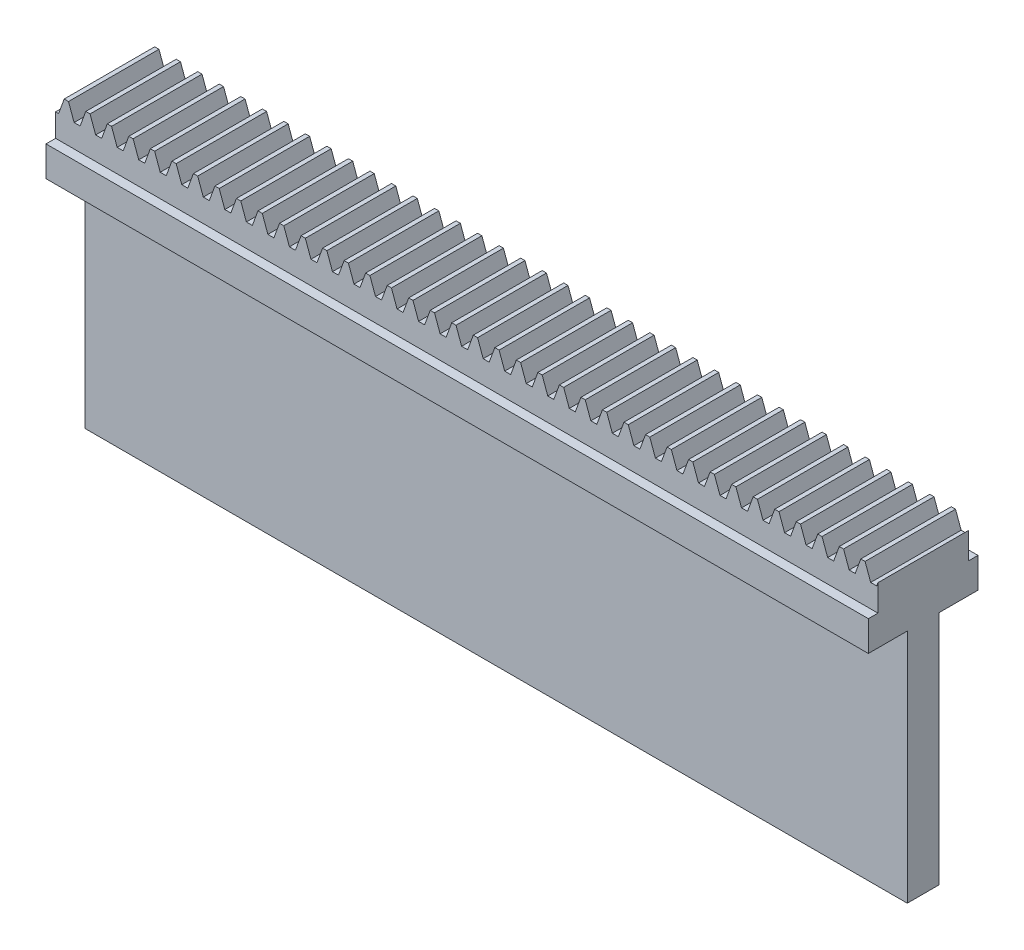
SolidWorks part; units mm, degrees
extrude "Blank" add sketch "BlankSke" against normal blind 20
sketch "BlankSke" plane through (0, 0, 0) normal (0, 0, 1) x (1, 0, 0)
  line L1 (0, 0) -> (150, 0)
  line L2 (0, 0) -> (0, 12.5)
  line L3 (0, 12.5) -> (150, 12.5)
  line L4 (150, 0) -> (150, 12.5)
  dimension "Length" = 150
  dimension "Blank_height" = 12.5
ref_plane "Plane1" through (0, 0, 0) normal (0, 0, 1) x (1, 0, 0)
ref_plane "Plane2" through (0, 0, 0) normal (0, 1, 0) x (1, 0, 0)
ref_plane "Plane3" through (0, 0, 0) normal (1, 0, 0) x (0, 0, -1)
other "Configuration Table"
sketch "HoldingSke" plane through (0, 0, 0) normal (0, 1, 0) x (1, 0, 0)
  line L0 (0, 0) -> (0.1113, 0.7922)
  line L1 (-15, 0) -> (100, 0) construction
  line L2 (0, 0) -> (-2.1039, 2.3779)
  line L3 (0, 0) -> (-11.863, 4.5341)
  line L4 (0, 0) -> (6.6156, 5.5511)
  line L5 (0, 0) -> (-23.7986, -8.8762)
  line L6 (0, 0) -> (-10.5278, -7.1032)
  line L9 (-71.009, 38.7566) -> (69.9449, 90.0596)
  line L10 (-76.2, 3.6279) -> (-64.95, 3.6279)
  line L11 (0, 0) -> (-7, 0)
  line L12 (-76.2, 101.6) -> (-76.155, 101.6)
  line L13 (24.9733, 27.94) -> (52.9518, 28.4284)
  line L14 (24.9733, 27.94) -> (24.9743, 27.94)
  line L15 (24.9733, 27.94) -> (100.4006, 29.5858)
  circle A0 centre (0, 0) radius 19.05
  circle A1 centre (0, 0) radius 5.625
  circle A2 centre (0, 0) radius 12.7
  dimension "MPH" = 11.25
  dimension "Diameter" = 38.1
  dimension "Num_teeth" = 40
  dimension "Pitch" = 0.8
  dimension "Show_teeth" = 998
  dimension "Thickness" = 12.7
  dimension "Ap" = 20
  dimension "Pitch_height" = 11.25
  dimension "Width" = 7
  dimension "Backlash" = 0.045
  dimension "Addendum_fac" = 1
  dimension "Dedendum_fac" = 1.25
  dimension "Clearance_fac" = 0.25
  dimension "Dedendum_add" = 0.001
  dimension "Length" = 150
  dimension "Module" = 1.25
sketch "TooCutSkeIll" plane through (0, 0, 0) normal (0, 0, 1) x (1, 0, 0)
  line L0 (-1.5597, 12.4671) -> (-0.6231, 9.8938)
  line L1 (-0.3285, 9.6875) -> (0.3285, 9.6875)
  line L2 (0.6231, 9.8938) -> (1.5597, 12.4671)
  line L3 (150, 12.5) -> (0, 12.5) construction
  line L4 (0, 0) -> (0, 64.897) construction
  line L5 (-13.208, 11.25) -> (12.954, 11.25) construction
  line L6 (0, 0) -> (150, 0) construction
  line L7 (1.1167, 11.25) -> (1.1167, 48.7463) construction
  line L8 (-1.1167, 11.25) -> (-1.1167, 48.7463) construction
  line L9 (1.6067, 12.5) -> (1.6067, 12.5254)
  line L10 (-1.6067, 12.5) -> (-1.6067, 12.5254)
  line L11 (-1.6067, 12.5254) -> (1.6067, 12.5254)
  arc A0 (0.3285, 9.6875) -> (0.6231, 9.8938) centre (0.3285, 10.001) ccw
  arc A1 (-0.6231, 9.8938) -> (-0.3285, 9.6875) centre (-0.3285, 10.001) ccw
  arc A2 (1.6067, 12.5) -> (1.5597, 12.4671) centre (1.6067, 12.45) ccw
  arc A3 (-1.5597, 12.4671) -> (-1.6067, 12.5) centre (-1.6067, 12.45) ccw
  dimension "Pitch_height" = 11.25
  dimension "Addendum_plus" = 1.2754
  dimension "Pressure_angle" = 20
  dimension "Gap_width" = 2.2335
  dimension "Dedendum" = 1.5625
extrude "ToothCutIll" [suppressed] cut sketch "TooCutSkeIll" against normal through all
sketch "TooCutSkeSim" plane through (0, 0, 0) normal (0, 0, 1) x (1, 0, 0)
  line L0 (0.548, 9.6875) -> (-0.548, 9.6875)
  line L1 (1.581, 12.5254) -> (0.548, 9.6875)
  line L2 (0, 17.4625) -> (0, 53.467) construction
  line L3 (1.581, 12.5254) -> (-1.581, 12.5254)
  line L6 (-1.581, 12.5254) -> (-0.548, 9.6875)
  line L9 (-1.1167, 11.25) -> (1.1167, 11.25) construction
  line L10 (0, 0) -> (150, 0) construction
  line L11 (1.1167, 11.25) -> (1.1167, 53.467) construction
  line L12 (-1.1167, 11.25) -> (-1.1167, 53.467) construction
  dimension "Pitch_height" = 11.25
  dimension "Addendum_plus" = 1.2754
  dimension "Pressure_angle" = 20
  dimension "Gap_width" = 2.2335
  dimension "Dedendum" = 1.5625
extrude "ToothCutSim" cut sketch "TooCutSkeSim" against normal through all
pattern_linear "TeethCuts" count 39 spacing 3.927 along (1, 0, 0) of "ToothCutIll", "ToothCutSim"
sketch "Croquis3" plane through (0, 0, 0) normal (0, 0, 1) x (1, 0, 0)
  line L0 (0, 9.6875) -> (0, 0) construction
  line L1 (0, 5.5) -> (150.5773, 5.5)
  line L2 (0, 5.5) -> (0, 12.8527)
  line L3 (0, 12.8527) -> (150.5773, 12.8527)
  line L4 (150.5773, 5.5) -> (150.5773, 12.8527)
  line L5 (123.408, 0) -> (123.408, 5.5) construction
  line L6 (0, 0) -> (150, 0) construction
  dimension "D1" = 5.5
extrude "Cortar-Extruir1" cut sketch "Croquis3" against normal blind 1.75
sketch "Croquis4" plane through (0, 0, -20) normal (0, 0, -1) x (-1, 0, 0)
  line L0 (-150, 0) -> (-150, 10.3093) construction
  line L1 (-150, 5.5) -> (0, 5.5)
  line L2 (-150, 5.5) -> (-150, 14.4015)
  line L3 (-150, 14.4015) -> (0, 14.4015)
  line L4 (0, 5.5) -> (0, 14.4015)
  line L5 (0, 0) -> (-150, 0) construction
  dimension "D1" = 5.5
extrude "Cortar-Extruir2" cut sketch "Croquis4" against normal blind 1.75
sketch "Croquis5" plane through (150, 0, 0) normal (1, 0, 0) x (0, 0, -1)
  line L0 (0, 0) -> (18.25, 10.3093) construction
  line L1 (18.25, 10.3093) -> (1.75, 10.3093) construction
  line L2 (1.75, 10.3093) -> (20, 0) construction
  circle A0 centre (10, 5.6489) radius 2
  dimension "D1" = 4
sketch "Croquis6" plane through (0, 0, 0) normal (0, -1, 0) x (1, 0, 0)
  line L6 (0, -20) -> (0, 0) construction
  line L8 (0, -7.1) -> (150, -7.1)
  line L9 (0, -7.1) -> (0, -12.9)
  line L11 (0, -12.9) -> (150, -12.9)
  line L12 (150, -7.1) -> (150, -12.9)
  line L13 (150, -20) -> (150, 0) construction
  line L14 (25.8218, 0) -> (25.8218, -7.1) construction
  line L15 (0, 0) -> (150, 0) construction
  line L16 (25.8218, -7.1) -> (32.7674, -12.9) construction
  line L17 (32.7674, -12.9) -> (32.7674, -20) construction
  line L18 (0, -20) -> (150, -20) construction
  dimension "D1" = 5.8
extrude "Saliente-Extruir1" add sketch "Croquis6" along normal blind 43
sketch "Croquis7" plane through (0, 0, -12.9) normal (0, 0, -1) x (-1, 0, 0)
  line L0 (-139.5463, -43) -> (-139.5463, 0) construction
  line L1 (0, -43) -> (-150, -43) construction
  line L2 (0, 0) -> (-150, 0) construction
equation "' \"Module@HoldingSke\" = 6.35"
equation "' \"Num_teeth@HoldingSke\" = 12"
equation "' \"Ap@HoldingSke\" =  20"
equation "' \"Ap@HoldingSke\" = 20"
equation "' \"Width@HoldingSke\" = 0.25 * 25.4"
equation "' \"Show_teeth@HoldingSke\" = 500"
equation "' \"Backlash@HoldingSke\" = 0.009 * 25.4"
equation "' \"Addendum_fac@HoldingSke\" = 1.0"
equation "' \"Dedendum_fac@HoldingSke\" = 1.25"
equation "' \"Dedendum_add@HoldingSke\" = 0.00005 * 25.4"
equation "' \"Clearance_fac@HoldingSke\" = 0.25"
equation "' \"Pitch_height@HoldingSke\" = 1 * 25.4"
equation "' \"Length@HoldingSke\" = 4.71 * 25.4"
equation "\"Pitch@HoldingSke\" = 1 / \"Module@HoldingSke\""
equation "\"MPH@HoldingSke\" = \"Dedendum_fac@HoldingSke\" / \"Pitch@HoldingSke\" + 2 * \"Dedendum_add@HoldingSke\" + 0.002 * 25.4"
equation "\"MPH@HoldingSke\" = ((sgn( \"MPH@HoldingSke\" - \"Pitch_height@HoldingSke\")+1)*( \"MPH@HoldingSke\" - \"Pitch_height@HoldingSke\"))/2 + \"Pitch_height@HoldingSke\""
equation "\"Blank_height@BlankSke\" = \"Pitch_height@HoldingSke\" + \"Addendum_fac@HoldingSke\"  / \"Pitch@HoldingSke\" "
equation "\"Length@BlankSke\" =  \"Length@HoldingSke\""
equation "\"Pressure_angle@TooCutSkeIll\" = \"Ap@HoldingSke\""
equation "\"Addendum_plus@TooCutSkeIll\" =  \"Addendum_fac@HoldingSke\"  / \"Pitch@HoldingSke\" + 0.001 *25.4"
equation "\"Dedendum@TooCutSkeIll\" = \"Dedendum_fac@HoldingSke\"  / \"Pitch@HoldingSke\""
equation "\"Pitch_height@TooCutSkeIll\" =  \"MPH@HoldingSke\""
equation "\"Gap_width@TooCutSkeIll\" = 3.14159265 / 2 / \"Pitch@HoldingSke\" + 6 * \"Backlash@HoldingSke\""
equation "\"Pressure_angle@TooCutSkeSim\" = \"Ap@HoldingSke\""
equation "\"Addendum_plus@TooCutSkeSim\" =  \"Addendum_fac@HoldingSke\"  / \"Pitch@HoldingSke\" + 0.001 * 25.4"
equation "\"Dedendum@TooCutSkeSim\" = \"Dedendum_fac@HoldingSke\"  / \"Pitch@HoldingSke\""
equation "\"Pitch_height@TooCutSkeSim\" =  \"MPH@HoldingSke\""
equation "\"Gap_width@TooCutSkeSim\" = 3.14159265 / 2 / \"Pitch@HoldingSke\" + 6 * \"Backlash@HoldingSke\""
equation "\"Root_fillet@TooCutSkeIll\" = \"Clearance_fac@HoldingSke\" / \"Pitch@HoldingSke\" + \"Dedendum_add@HoldingSke\""
equation "\"Break_rad@TooCutSkeIll\" = 0.02 / \"Pitch@HoldingSke\" * 2"
equation "\"Linear_pitch@TeethCuts\" = 3.14159265 / \"Pitch@HoldingSke\""
equation "\"Num_teeth@HoldingSke\" = int( ( \"Length@HoldingSke\" + 0 ) / (3.14159265 / \"Pitch@HoldingSke\")) + 0.9999  + 1"
equation " \"Num_teeth@TeethCuts\" = int( \"Show_teeth@HoldingSke\" ) + 1"
equation " \"Num_teeth@TeethCuts\" = ((sgn( \"Num_teeth@TeethCuts\" - \"Num_teeth@HoldingSke\" )-1)*( \"Num_teeth@TeethCuts\" - \"Num_teeth@HoldingSke\" ))/-2+ \"Num_teeth@HoldingSke\""
equation " \"Num_teeth@TeethCuts\" = ((sgn( \"Num_teeth@TeethCuts\" - 2.0)+1)*( \"Num_teeth@TeethCuts\" - 2.0))/2 +2.0"
